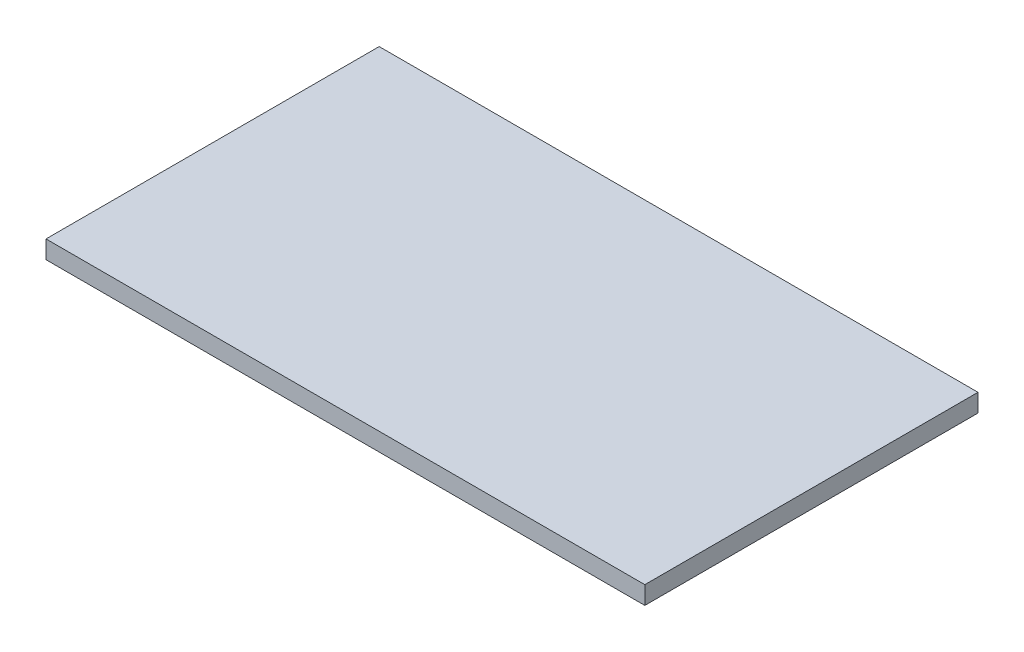
SolidWorks part; units mm, degrees
ref_plane "前视基准面" through (0, 0, 0) normal (0, 0, 1) x (1, 0, 0)
ref_plane "上视基准面" through (0, 0, 0) normal (0, 1, 0) x (1, 0, 0)
ref_plane "右视基准面" through (0, 0, 0) normal (1, 0, 0) x (0, 0, -1)
sketch "草图1" plane through (0, 0, 0) normal (0, 1, 0) x (1, 0, 0)
  line L1 (0, 0) -> (133, 0)
  line L2 (0, 0) -> (0, -74)
  line L3 (0, -74) -> (133, -74)
  line L4 (133, 0) -> (133, -74)
  dimension "D1" = 133
  dimension "D2" = 74
extrude "凸台-拉伸1" add sketch "草图1" along normal blind 4
